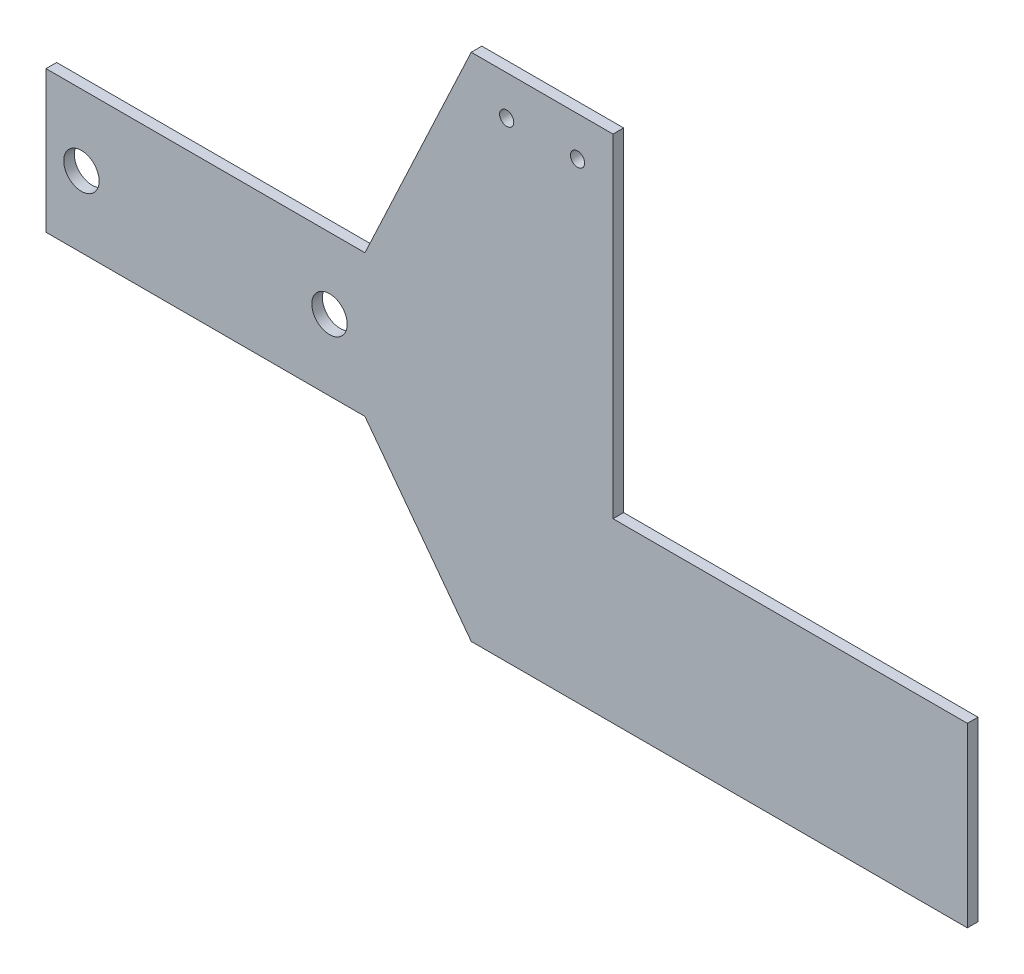
SolidWorks part; units mm, degrees
ref_plane "Front Plane" through (0, 0, 0) normal (0, 0, 1) x (1, 0, 0)
ref_plane "Top Plane" through (0, 0, 0) normal (0, 1, 0) x (1, 0, 0)
ref_plane "Right Plane" through (0, 0, 0) normal (1, 0, 0) x (0, 0, -1)
sketch "Sketch1" plane through (0, 0, 0) normal (0, 0, 1) x (1, 0, 0)
  line L1 (-20, 72) -> (0, 72)
  line L3 (-20, 0) -> (0, 0)
  line L6 (50, 25) -> (50, 0)
  line L7 (-35, 20) -> (-80, 20)
  line L8 (-35, 40) -> (-80, 40)
  line L9 (-80, 40) -> (-80, 20)
  line L12 (-20, 0) -> (-35, 20)
  line L13 (-20, 40) -> (-80, 40) construction
  line L14 (-20, 20) -> (-80, 20) construction
  line L15 (0, 25) -> (50, 25)
  line L16 (0, 0) -> (50, 0)
  line L17 (-20, 72) -> (0, 72)
  line L18 (0, 72) -> (0, 25)
  line L19 (-20, 72) -> (-35, 40)
  line L20 (-80, 30) -> (-35, 30)
  line L21 (-57.5, 40) -> (-57.5, 20)
  line L22 (-75, 40) -> (-75, 20)
  line L23 (-35, 36.9672) -> (-35, 24.3663)
  line L24 (-40, 36.9672) -> (-40, 24.3663)
  circle A0 centre (-5, 66.44) radius 1
  circle A1 centre (-15, 66.44) radius 1
  circle A2 centre (-75, 30) radius 2.5
  circle A3 centre (-40, 30) radius 2.5
  dimension "D11" = 5
  dimension "D12" = 5
  dimension "D13" = 2
  dimension "D1" = 72
  dimension "D2" = 20
  dimension "D3" = 50
  dimension "D4" = 25
  dimension "D6" = 20
  dimension "D7" = 40
  dimension "D9" = 5
  dimension "D10" = 5
  dimension "D5" = 45
  dimension "D8" = 32
  dimension "D14" = 5
  dimension "D15" = 15
  dimension "D16" = 66.44
extrude "Boss-Extrude1" add sketch "Sketch1" along normal blind 1.5
